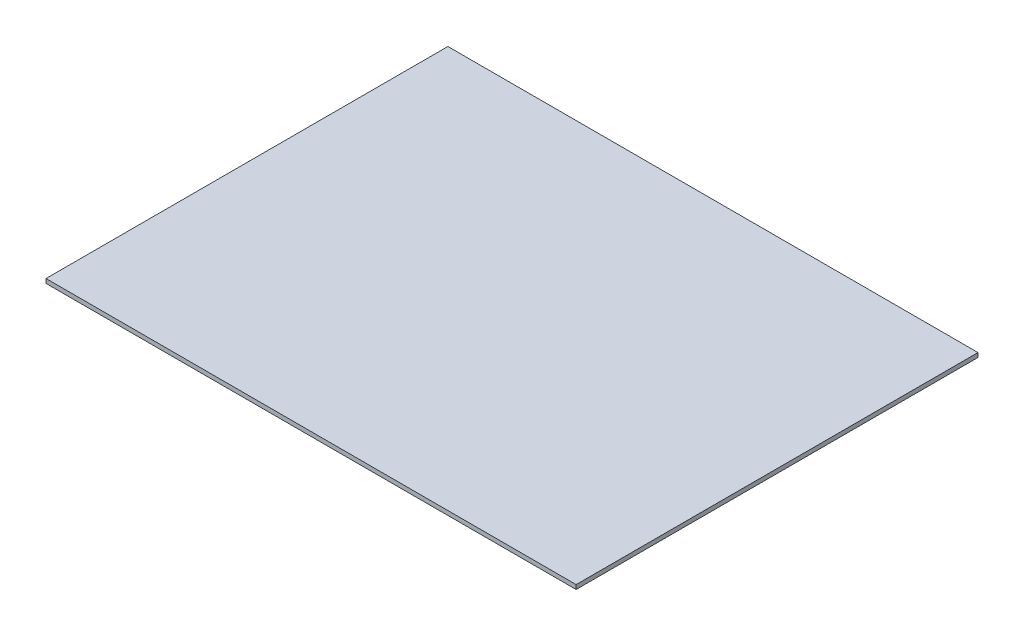
SolidWorks part; units mm, degrees
ref_plane "Front Plane" through (0, 0, 0) normal (0, 0, 1) x (1, 0, 0)
ref_plane "Top Plane" through (0, 0, 0) normal (0, 1, 0) x (1, 0, 0)
ref_plane "Right Plane" through (0, 0, 0) normal (1, 0, 0) x (0, 0, -1)
sketch "Sketch1" plane through (0, 0, 0) normal (0, 1, 0) x (1, 0, 0)
  line L1 (-787.4, -596.9) -> (787.4, -596.9)
  line L2 (-787.4, -596.9) -> (-787.4, 596.9)
  line L3 (-787.4, 596.9) -> (787.4, 596.9)
  line L4 (787.4, -596.9) -> (787.4, 596.9)
  line L5 (-787.4, -596.9) -> (787.4, 596.9) construction
  line L6 (-787.4, 596.9) -> (787.4, -596.9) construction
  point P0 (0, 0)
  dimension "D1" = 1574.8
  dimension "D2" = 1193.8
extrude "Boss-Extrude1" add sketch "Sketch1" along normal blind 12.7
